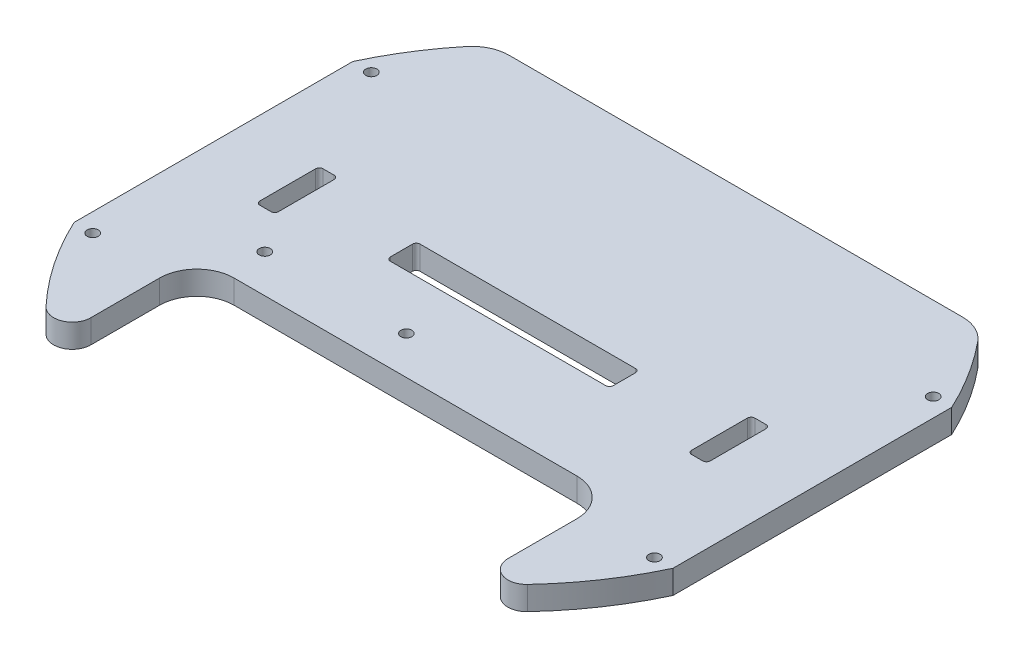
SolidWorks part; units mm, degrees
ref_plane "Front Plane" through (0, 0, 0) normal (0, 0, 1) x (1, 0, 0)
ref_plane "Top Plane" through (0, 0, 0) normal (0, 1, 0) x (1, 0, 0)
ref_plane "Right Plane" through (0, 0, 0) normal (1, 0, 0) x (0, 0, -1)
sketch "Sketch1" plane through (0, 0, 0) normal (0, 1, 0) x (1, 0, 0)
  line L0 (-80.6037, 37.5) -> (-80.6037, -37.5)
  line L1 (0, -88.9) -> (0, 88.9) construction
  line L2 (80.6037, 37.5) -> (80.6037, -37.5)
  arc A0 (-80.6037, -37.5) -> (80.6037, -37.5) centre (0, 0) ccw
  arc A1 (80.6037, 37.5) -> (-80.6037, 37.5) centre (0, 0) ccw
  dimension "D1" = 177.8
  dimension "D2" = 75
extrude "Main Body" add sketch "Sketch1" along normal blind 6.35
sketch "Sketch2" plane through (0, 6.35, 0) normal (0, 1, 0) x (1, 0, 0)
  line L0 (0, 88.9) -> (0, -88.9) construction
  line L1 (36.5, 69.85) -> (-21.5, 69.85) construction
  line L2 (36.5, 69.85) -> (36.5, 20.85) construction
  line L3 (36.5, 20.85) -> (-21.5, 20.85) construction
  line L4 (-21.5, 69.85) -> (-21.5, 20.85) construction
  line L5 (36.5, 69.85) -> (-21.5, 20.85) construction
  line L6 (36.5, 20.85) -> (-21.5, 69.85) construction
  line L7 (32.5, 20.85) -> (32.5, 69.85) construction
  line L8 (-25.5, 20.85) -> (-25.5, 69.85) construction
  circle A0 centre (36.5, 69.85) radius 1.524
  circle A1 centre (36.5, 20.85) radius 1.524
  circle A2 centre (-21.5, 20.85) radius 1.524
  circle A3 centre (-21.5, 69.85) radius 1.524
  arc A4 (-80.6037, -37.5) -> (80.6037, -37.5) centre (0, 0) ccw construction
  arc A5 (80.6037, 37.5) -> (-80.6037, 37.5) centre (0, 0) ccw construction
  circle A6 centre (32.5, 20.85) radius 1.1
  circle A7 centre (-25.5, 20.85) radius 1.1
  circle A8 centre (32.5, 69.85) radius 1.1
  circle A9 centre (-25.5, 69.85) radius 1.1
  point P0 (7.5, 45.35)
  point P11 (0, 88.9)
  dimension "D3" = 3.048
  dimension "D6" = 2.2
  dimension "D1" = 58
  dimension "D2" = 49
  dimension "D4" = 19.05
  dimension "D5" = 15
  dimension "D7" = 4
  dimension "D8" = 4
sketch "Sketch3" plane through (0, 6.35, 0) normal (0, 1, 0) x (1, 0, 0)
  line L0 (-80.6037, 0) -> (80.6037, 0) construction
  line L1 (-80.6037, 37.5) -> (-80.6037, -37.5) construction
  line L2 (80.6037, -37.5) -> (80.6037, 37.5) construction
  line L3 (-74.3537, -9) -> (-74.3537, 9) construction
  line L4 (0, -88.9) -> (0, 88.9) construction
  line L5 (74.3537, -9) -> (74.3537, 9) construction
  circle A0 centre (-74.3537, 9) radius 1.143
  circle A1 centre (-74.3537, -9) radius 1.143
  arc A2 (-80.6037, -37.5) -> (80.6037, -37.5) centre (0, 0) ccw construction
  arc A3 (80.6037, 37.5) -> (-80.6037, 37.5) centre (0, 0) ccw construction
  circle A4 centre (74.3537, 9) radius 1.143
  circle A5 centre (74.3537, -9) radius 1.143
  point P10 (-74.3537, 0)
  point P19 (74.3537, 0)
  dimension "D1" = 6.25
  dimension "D2" = 2.286
  dimension "D3" = 18
sketch "Sketch4" plane through (0, 6.35, 0) normal (0, 1, 0) x (1, 0, 0)
  line L0 (0, -88.9) -> (0, 88.9) construction
  line L1 (-7.747, 78.9) -> (7.747, 78.9) construction
  arc A0 (-80.6037, -37.5) -> (80.6037, -37.5) centre (0, 0) ccw construction
  arc A1 (80.6037, 37.5) -> (-80.6037, 37.5) centre (0, 0) ccw construction
  circle A2 centre (-7.747, 78.9) radius 1.524
  circle A3 centre (7.747, 78.9) radius 1.524
  point P10 (0, 78.9)
  dimension "D1" = 3.048
  dimension "D2" = 15.494
  dimension "D3" = 10
sketch "Sketch5" plane through (0, 6.35, 0) normal (0, 1, 0) x (1, 0, 0)
  line L0 (0, -88.9) -> (0, 88.9) construction
  line L1 (29.21, -82.5485) -> (29.21, 0.1133) construction
  line L2 (29.21, -24.4861) -> (50029.21, -24.4861) construction
  line L3 (29.21, -28.2961) -> (56.134, -28.2961) construction
  line L4 (29.21, -28.2961) -> (29.21, -68.9361) construction
  line L5 (29.21, -68.9361) -> (56.134, -68.9361) construction
  line L6 (56.134, -28.2961) -> (56.134, -68.9361) construction
  line L7 (29.21, -72.7461) -> (50029.21, -72.7461) construction
  line L8 (29.21, -28.2961) -> (29.21, -24.4861) construction
  line L9 (29.21, -68.9361) -> (29.21, -72.7461) construction
  line L10 (35.56, -24.4861) -> (35.56, -72.7461) construction
  arc A0 (-80.6037, -37.5) -> (80.6037, -37.5) centre (0, 0) ccw construction
  arc A1 (80.6037, 37.5) -> (-80.6037, 37.5) centre (0, 0) ccw construction
  circle A2 centre (35.56, -24.4861) radius 1.524
  circle A3 centre (35.56, -72.7461) radius 1.524
  dimension "D4" = 3.048
  dimension "D1" = 29.21
  dimension "D2" = 40.64
  dimension "D3" = 26.924
  dimension "D5" = 6.35
  dimension "D6" = 48.26
sketch "Sketch6" plane through (0, 6.35, 0) normal (0, 1, 0) x (1, 0, 0)
  line L0 (0, -88.1692) -> (0, -5.66) construction
  line L2 (-26.543, -75.692) -> (26.543, -75.692) construction
  line L3 (-26.543, -75.692) -> (-26.543, -63.5) construction
  line L4 (-26.543, -63.5) -> (26.543, -63.5) construction
  line L5 (26.543, -75.692) -> (26.543, -63.5) construction
  line L6 (-26.543, -75.692) -> (26.543, -63.5) construction
  line L7 (-26.543, -63.5) -> (26.543, -75.692) construction
  circle A0 centre (-12.7, -69.596) radius 1.524
  circle A1 centre (12.7, -69.596) radius 1.524
  point P1 (0, -69.596)
  dimension "D4" = 3.048
  dimension "D1" = 63.5
  dimension "D2" = 12.192
  dimension "D3" = 53.086
  dimension "D5" = 25.4
  dimension "D6" = 12.7
extrude "Front IR" cut sketch "Sketch6" against normal through all
sketch "Sketch8" plane through (0, 6.35, 0) normal (0, 1, 0) x (1, 0, 0)
  line L0 (0, 0) -> (0, 88.9) construction
  line L1 (-80.6037, 37.5) -> (-80.6037, -37.5) construction
  line L2 (-80.6037, -29.88) -> (80.6037, -29.88) construction
  line L3 (80.6037, -37.5) -> (80.6037, 37.5) construction
  line L4 (-80.6037, 23.206) -> (80.6037, 23.206) construction
  line L5 (0, 23.206) -> (0, -29.88) construction
  line L6 (0, -29.88) -> (0, -3.337) construction
  line L7 (-63.5, -37.5) -> (63.5, -37.5) construction
  circle A1 centre (-63.5, -37.5) radius 1.524
  circle A2 centre (-63.5, -50.2) radius 1.524
  circle A3 centre (63.5, -50.2) radius 1.524
  circle A4 centre (63.5, -37.5) radius 1.524
  dimension "D3" = 3.048
  dimension "D1" = 53.086
  dimension "D2" = 7.62
  dimension "D4" = 12.7
  dimension "D5" = 63.5
  dimension "D6" = 7.62
sketch "Sketch10" plane through (0, 6.35, 0) normal (0, 1, 0) x (1, 0, 0)
  line L0 (0, -88.9) -> (0, 0) construction
  line L1 (19.05, -101.854) -> (19.05, -75.946)
  line L2 (19.05, -101.854) -> (-19.05, -101.854)
  line L3 (19.05, -75.946) -> (-19.05, -75.946)
  line L4 (-19.05, -101.854) -> (-19.05, -75.946)
  line L5 (19.05, -101.854) -> (-19.05, -75.946) construction
  line L6 (19.05, -75.946) -> (-19.05, -101.854) construction
  arc A0 (-80.6037, -37.5) -> (80.6037, -37.5) centre (0, 0) ccw construction
  circle A1 centre (-12.7, -69.596) radius 1.524 construction
  dimension "D2" = 6.35
  dimension "D1" = 38.1
extrude "Grabber slot" cut sketch "Sketch10" against normal through all
sketch "Sketch11" plane through (0, 6.35, 0) normal (0, 1, 0) x (1, 0, 0)
  line L0 (0, 88.9) -> (0, -75.946) construction
  line L1 (19.05, -75.946) -> (-19.05, -75.946) construction
  line L2 (80.6037, 0) -> (-80.6037, 0) construction
  line L3 (80.6037, -37.5) -> (80.6037, 37.5) construction
  line L4 (-80.6037, 37.5) -> (-80.6037, -37.5) construction
  line L5 (-60.6037, 8.5) -> (-55.6037, 8.5)
  line L6 (30, -4) -> (-30, -4)
  line L7 (30, -4) -> (30, 4)
  line L8 (30, 4) -> (-30, 4)
  line L9 (-30, -4) -> (-30, 4)
  line L10 (30, -4) -> (-30, 4) construction
  line L11 (30, 4) -> (-30, -4) construction
  line L12 (60.6037, -8.5) -> (55.6037, -8.5)
  line L13 (60.6037, -8.5) -> (60.6037, 8.5)
  line L14 (60.6037, 8.5) -> (55.6037, 8.5)
  line L15 (55.6037, -8.5) -> (55.6037, 8.5)
  line L16 (60.6037, -8.5) -> (55.6037, 8.5) construction
  line L17 (60.6037, 8.5) -> (55.6037, -8.5) construction
  line L18 (-55.6037, -8.5) -> (-55.6037, 8.5)
  line L19 (-60.6037, -8.5) -> (-55.6037, -8.5)
  line L20 (-60.6037, -8.5) -> (-60.6037, 8.5)
  arc A0 (80.6037, 37.5) -> (-80.6037, 37.5) centre (0, 0) ccw construction
  point P13 (0, 0)
  point P19 (58.1037, 0)
  dimension "D3" = 20
  dimension "D1" = 8
  dimension "D2" = 60
  dimension "D4" = 17
  dimension "D5" = 5
extrude "Wire slots" cut sketch "Sketch11" against normal through all
sketch "Sketch13" plane through (0, 6.35, 0) normal (0, 1, 0) x (1, 0, 0)
  line L0 (0, 88.9) -> (0, -75.946) construction
  line L1 (19.05, -75.946) -> (-19.05, -75.946) construction
  line L2 (80.6037, 0) -> (-80.6037, 0) construction
  line L3 (80.6037, -37.5) -> (80.6037, 37.5) construction
  line L4 (-80.6037, 37.5) -> (-80.6037, -37.5) construction
  line L5 (80.6037, -37.5) -> (-80.6037, -37.5) construction
  line L6 (80.6037, 37.5) -> (-80.6037, 37.5) construction
  line L8 (75.6037, 37.5) -> (-75.6037, 37.5) construction
  line L9 (75.6037, 37.5) -> (75.6037, -37.5) construction
  line L10 (75.6037, -37.5) -> (-75.6037, -37.5) construction
  line L11 (-75.6037, 37.5) -> (-75.6037, -37.5) construction
  line L12 (75.6037, 37.5) -> (-75.6037, -37.5) construction
  line L13 (75.6037, -37.5) -> (-75.6037, 37.5) construction
  arc A0 (80.6037, 37.5) -> (-80.6037, 37.5) centre (0, 0) ccw construction
  circle A1 centre (75.6037, -37.5) radius 1.5
  circle A2 centre (-75.6037, -37.5) radius 1.5
  circle A3 centre (75.6037, 37.5) radius 1.5
  circle A4 centre (-75.6037, 37.5) radius 1.5
  point P21 (0, 0)
  dimension "D2" = 3
  dimension "D1" = 5
extrude "2nd level" cut sketch "Sketch13" against normal through all
sketch "Sketch14" plane through (0, 6.35, 0) normal (0, 1, 0) x (1, 0, 0)
  line L0 (56.134, -68.9361) -> (56.134, -28.9361)
  line L1 (56.134, -28.9361) -> (-56.134, -28.9361)
  line L2 (-56.134, -28.9361) -> (-56.134, -68.9361)
  line L3 (19.05, -86.8349) -> (19.05, -75.946) construction
  line L4 (19.05, -75.946) -> (-19.05, -75.946) construction
  line L5 (-19.05, -75.946) -> (-19.05, -86.8349) construction
  line L6 (19.05, -86.8349) -> (19.05, -75.946)
  line L7 (19.05, -75.946) -> (-19.05, -75.946)
  line L8 (-19.05, -75.946) -> (-19.05, -86.8349)
  arc A0 (-80.6037, -37.5) -> (-19.05, -86.8349) centre (0, 0) ccw construction
  arc A1 (19.05, -86.8349) -> (80.6037, -37.5) centre (0, 0) ccw construction
  arc A2 (19.05, -86.8349) -> (56.134, -68.9361) centre (0, 0) ccw
  arc A3 (-56.134, -68.9361) -> (-19.05, -86.8349) centre (0, 0) ccw
  dimension "D1" = 40
extrude "Cut-Extrude1" cut sketch "Sketch14" against normal through all
fillet "Fillet1" radius 5 2 edges at (-56.134, 3.175, 68.9361) (56.134, 3.175, 68.9361)
fillet "Fillet2" radius 10 2 edges at (-56.134, 3.175, 28.9361) (56.134, 3.175, 28.9361)
sketch "Sketch16" plane through (0, 6.35, 0) normal (0, 1, 0) x (1, 0, 0)
  line L0 (65.5989, 60) -> (-65.5989, 60)
  arc A0 (80.6037, 37.5) -> (-80.6037, 37.5) centre (0, 0) ccw construction
  arc A1 (65.5989, 60) -> (-65.5989, 60) centre (0, 0) ccw
  dimension "D1" = 60
extrude "Cut-Extrude2" cut sketch "Sketch16" against normal blind 10
fillet "Fillet3" radius 10 2 edges at (-65.5989, 3.175, -60) (65.5989, 3.175, -60)
fillet "Fillet4" radius 1 12 edges at (-60.6037, 3.175, 8.5) (-60.6037, 3.175, -8.5) (-55.6037, 3.175, 8.5) (-55.6037, 3.175, -8.5) (55.6037, 3.175, 8.5) (55.6037, 3.175, -8.5) (60.6037, 3.175, -8.5) (60.6037, 3.175, 8.5) (30, 3.175, 4) (30, 3.175, -4) (-30, 3.175, 4) (-30, 3.175, -4)
sketch "Sketch17" plane through (0, 6.35, 0) normal (0, 1, 0) x (1, 0, 0)
  line L0 (-80.6037, -18.6787) -> (80.6037, -18.6787) construction
  line L1 (-80.6037, 37.5) -> (-80.6037, -37.5) construction
  line L2 (80.6037, -37.5) -> (80.6037, 37.5) construction
  line L3 (0, 88.9) -> (0, -88.9) construction
  circle A0 centre (-48.1, -18.6787) radius 1.5
  circle A1 centre (-10, -18.6787) radius 1.5
  dimension "D2" = 3
  dimension "D1" = 38.1
  dimension "D3" = 10
extrude "Cut-Extrude3" cut sketch "Sketch17" against normal through all
